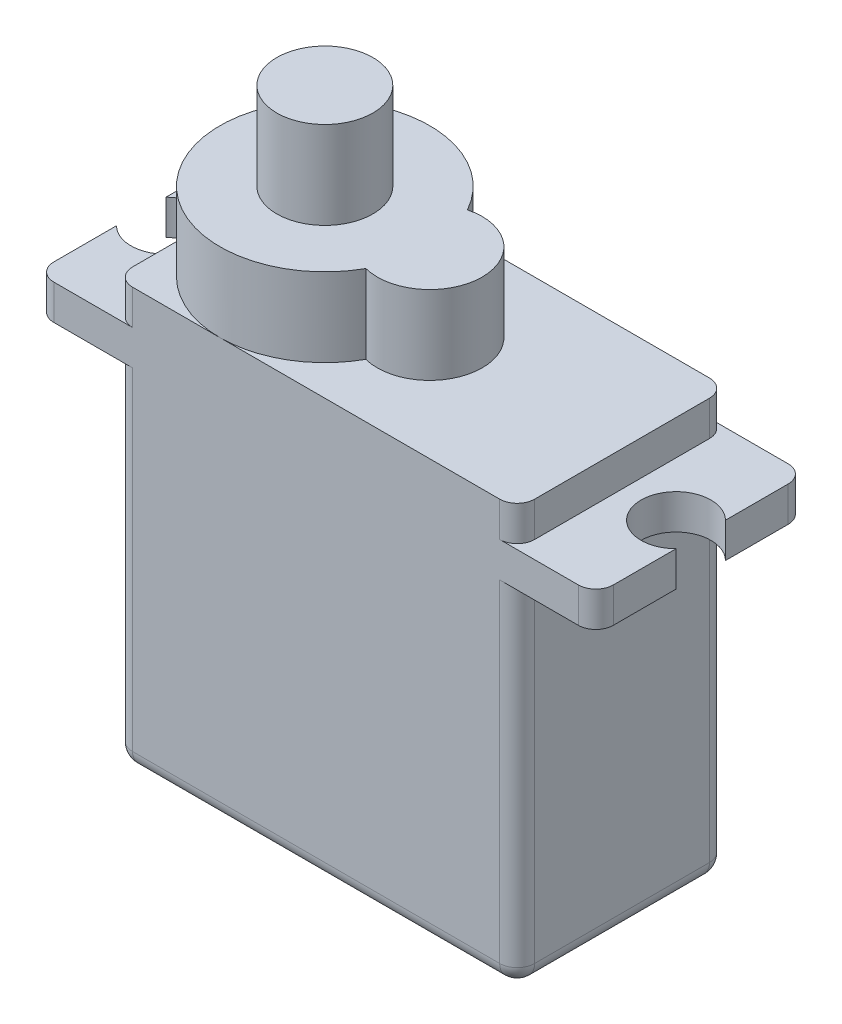
SolidWorks part; units mm, degrees
ref_plane "Front" through (0, 0, 0) normal (0, 0, 1) x (1, 0, 0)
ref_plane "Top" through (0, 0, 0) normal (0, 1, 0) x (1, 0, 0)
ref_plane "Right" through (0, 0, 0) normal (1, 0, 0) x (0, 0, -1)
sketch "Sketch1" plane through (0, 0, 0) normal (0, 1, 0) x (1, 0, 0)
  line L1 (-11.5, -6) -> (11.5, -6)
  line L2 (-11.5, -6) -> (-11.5, 6)
  line L3 (-11.5, 6) -> (11.5, 6)
  line L4 (11.5, -6) -> (11.5, 6)
  line L5 (-11.5, -6) -> (11.5, 6) construction
  line L6 (-11.5, 6) -> (11.5, -6) construction
  point P0 (0, 0)
  dimension "D1" = 23
  dimension "D2" = 12
extrude "Boss-Extrude1" add sketch "Sketch1" along normal blind 20
sketch "Sketch2" plane through (0, 20, 0) normal (0, 1, 0) x (1, 0, 0)
  line L0 (-16.3358, 0) -> (24.1642, 0) construction
  line L1 (-16, 6) -> (16, 6)
  line L2 (-16, 6) -> (-16, 1.4142)
  line L3 (-16, -6) -> (16, -6)
  line L4 (16, 6) -> (16, 1.4142)
  line L5 (-16, 6) -> (16, -6) construction
  line L6 (-16, -6) -> (16, 6) construction
  line L7 (0, 6) -> (0, -6) construction
  line L9 (-16, -1.4142) -> (-16, -6)
  line L10 (16, -1.4142) -> (16, -6)
  arc A0 (-16, -1.4142) -> (-16, 1.4142) centre (-14.5858, 0) ccw
  arc A1 (16, -1.4142) -> (16, 1.4142) centre (14.5858, 0) cw
  point P0 (0, 0)
  dimension "D3" = 4
  dimension "D2" = 12
  dimension "D5" = 32
extrude "Boss-Extrude2" add sketch "Sketch2" along normal blind 2
sketch "Sketch3" plane through (0, 22, 0) normal (0, 1, 0) x (1, 0, 0)
  line L0 (-16, -6) -> (16, -6) construction
  line L1 (-11.5, 6) -> (11.5, 6)
  line L2 (-11.5, 6) -> (-11.5, -6)
  line L3 (-11.5, -6) -> (11.5, -6)
  line L4 (11.5, 6) -> (11.5, -6)
  line L5 (-11.5, 6) -> (11.5, -6) construction
  line L6 (-11.5, -6) -> (11.5, 6) construction
  point P0 (0, 0)
  dimension "D1" = 23
extrude "Boss-Extrude3" add sketch "Sketch3" along normal blind 2
sketch "Sketch4" plane through (0, 24, 0) normal (0, 1, 0) x (1, 0, 0)
  line L0 (-14.5858, 0) -> (18.5063, 0) construction
  line L1 (-11.5, 6) -> (-11.5, -6) construction
  arc A0 (-0.25, 2.9047) -> (-0.25, -2.9047) centre (-5.5, 0) ccw
  arc A1 (-0.25, -2.9047) -> (-0.25, 2.9047) centre (0.5, 0) ccw
  dimension "D2" = 12
  dimension "D4" = 6
  dimension "D3" = 6
  dimension "D1" = 6
extrude "Boss-Extrude4" add sketch "Sketch4" along normal blind 4.5
sketch "Sketch5" plane through (0, 28.5, 0) normal (0, 1, 0) x (1, 0, 0)
  line L0 (-11.5, 6) -> (-11.5, 0) construction
  circle A0 centre (-5.5, 0) radius 2.75
  dimension "D2" = 5.5
  dimension "D1" = 6
extrude "Boss-Extrude5" add sketch "Sketch5" along normal blind 5
fillet "Fillet1" radius 1 16 edges at (-11.5, 0, 0) (0, 0, -6) (11.5, 0, 0) (0, 0, 6) (11.5, 23, -6) (11.5, 23, 6) (-11.5, 23, 6) (-11.5, 23, -6) (16, 21, 6) (16, 21, -6) (-16, 21, -6) (-16, 21, 6) (-11.5, 10, -6) (11.5, 10, -6) (11.5, 10, 6) (-11.5, 10, 6)
